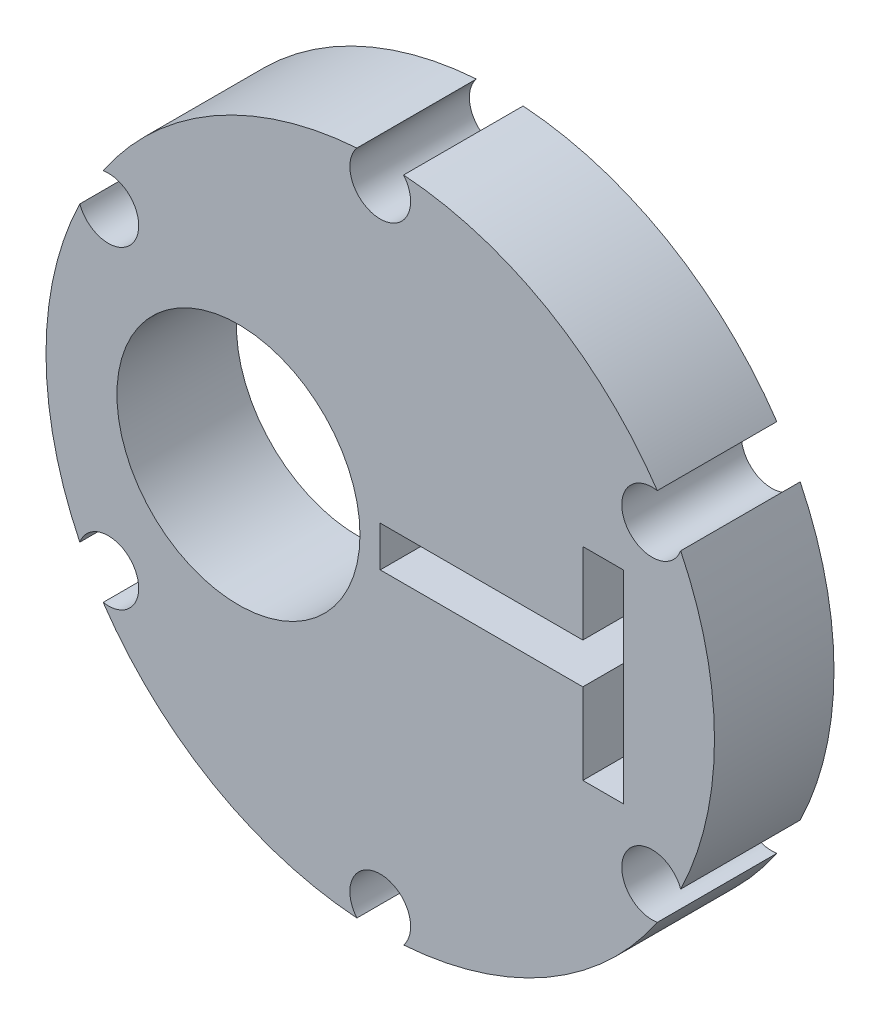
SolidWorks part; units mm, degrees
ref_plane "Front Plane" through (0, 0, 0) normal (0, 0, 1) x (1, 0, 0)
ref_plane "Top Plane" through (0, 0, 0) normal (0, 1, 0) x (1, 0, 0)
ref_plane "Right Plane" through (0, 0, 0) normal (1, 0, 0) x (0, 0, -1)
sketch "Sketch1" plane through (0, 0, 0) normal (0, 0, 1) x (1, 0, 0)
  circle A0 centre (0, 0) radius 16.5
  dimension "D1" = 33
extrude "Boss-Extrude1" add sketch "Sketch1" along normal blind 5.9
sketch "Sketch2" plane through (0, 0, 5.9) normal (0, 0, 1) x (1, 0, 0)
  circle A0 centre (0, 15.5) radius 1.5
  circle A1 centre (13.4234, 7.75) radius 1.5
  circle A2 centre (13.4234, -7.75) radius 1.5
  circle A3 centre (0, -15.5) radius 1.5
  circle A4 centre (-13.4234, -7.75) radius 1.5
  circle A5 centre (-13.4234, 7.75) radius 1.5
  point P15 (0, 0)
  dimension "D1" = 3
  dimension "D2" = 15.5
  dimension "D3" = 6
extrude "Cut-Extrude1" cut sketch "Sketch2" against normal through all
sketch "Sketch3" plane through (0, 0, 5.9) normal (0, 0, 1) x (1, 0, 0)
  line L0 (-7, 0) -> (0, 0) construction
  circle A0 centre (-7, 0) radius 6
  dimension "D1" = 12
  dimension "D3" = 7
extrude "Cut-Extrude2" cut sketch "Sketch3" against normal through all
sketch "Sketch5" plane through (0, 0, 5.9) normal (0, 0, 1) x (1, 0, 0)
  line L1 (12, 5) -> (10, 5)
  line L2 (12, 5) -> (12, -5)
  line L3 (12, -5) -> (10, -5)
  line L4 (10, 5) -> (10, 1)
  line L5 (10, -1) -> (10, -5)
  line L6 (0, 1) -> (10, 1)
  line L7 (0, 1) -> (0, -1)
  line L8 (0, -1) -> (10, -1)
  point P10 (0, 0)
  point P11 (0, 1)
  point P12 (10, 1)
  point P13 (0, 0)
  point P14 (10, 2.1322)
  point P15 (14.3221, 4.8238)
  dimension "D1" = 10
  dimension "D2" = 2
extrude "Cut-Extrude3" cut sketch "Sketch5" against normal through all
equation "\"smallPulleyTeeth\"= 15"
equation "\"largePulleyTeeth\"= 30"
equation "\"eighthThick\"= 2.9mm"
equation "\"sixteenthThick\" = 1.7mm"
equation "\"wheelEighthThick\"=3.0mm"
equation "\"quarterThick\"=5.9mm"
equation "\"OD\" = 145mm"
equation "\"puckAngle\" = 60.5deg"
equation "\"puckDiam\" = 76.5mm"
equation "\"axlePress\" = 5.9mm"
equation "\"D1@Boss-Extrude1\"=\"quarterThick\""
